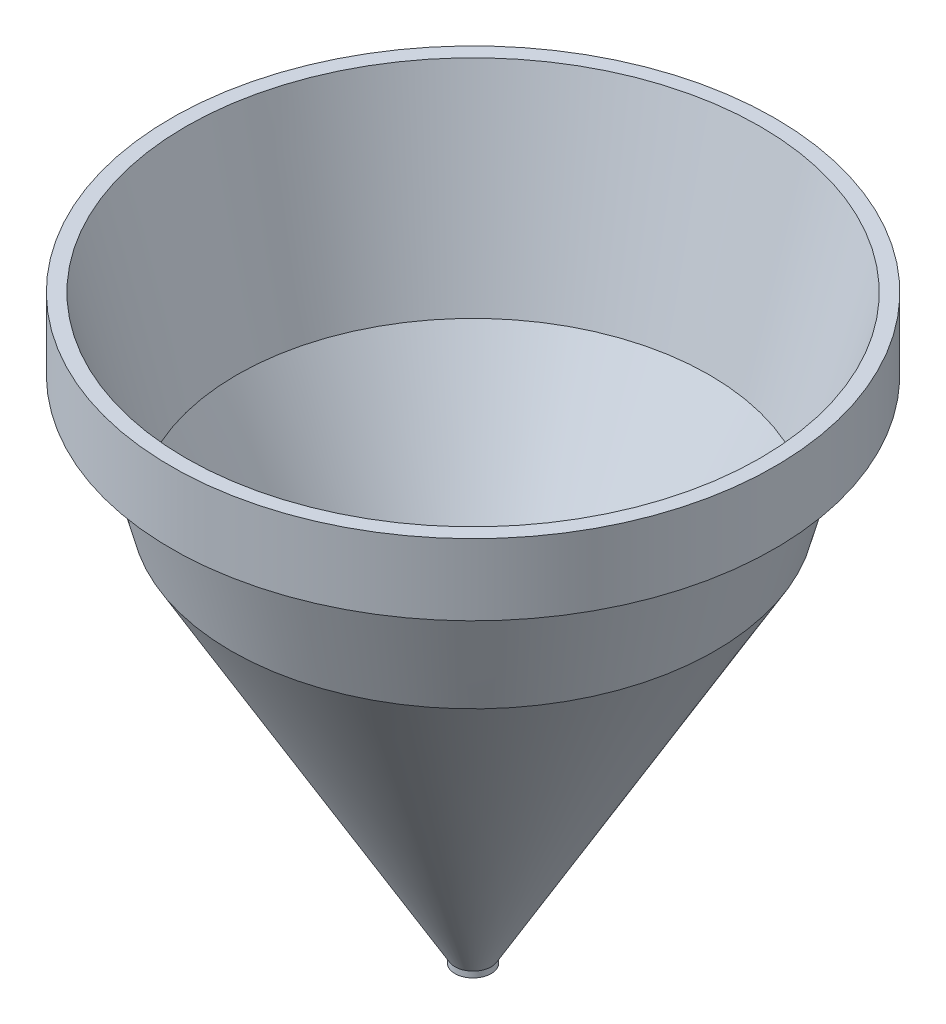
SolidWorks part; units mm, degrees
ref_plane "Piano frontale" through (0, 0, 0) normal (0, 0, 1) x (1, 0, 0)
ref_plane "Piano superiore" through (0, 0, 0) normal (0, 1, 0) x (1, 0, 0)
ref_plane "Piano destro" through (0, 0, 0) normal (1, 0, 0) x (0, 0, -1)
sketch "Schizzo1" plane through (0, 0, 0) normal (1, 0, 0) x (0, 0, -1)
  line L0 (0, 0) -> (0, 180) construction
  line L1 (0, 180) -> (-95, 180) construction
  line L2 (-95, 180) -> (-100, 180) construction
  line L3 (-95, 180) -> (-95, 130) construction
  line L4 (0, 0) -> (-4.25, 0) construction
  line L5 (-95, 180) -> (-81.6025, 130)
  line L6 (-100, 180) -> (-95, 180)
  line L7 (-100, 180) -> (-100, 170)
  line L8 (-100, 170) -> (-101.8, 170)
  line L9 (-101.8, 170) -> (-101.8, 194)
  line L10 (-93.2613, 180.4659) -> (-96.8878, 194)
  line L11 (-93.2613, 180.4659) -> (-79.739, 130)
  line L12 (-4.25, 0) -> (-79.739, 130)
  line L13 (-93.2613, 180.4659) -> (-105.0613, 224.5041) construction
  line L14 (-95, 180) -> (-106.8, 224.0382) construction
  line L15 (-95, 130) -> (-79.739, 130) construction
  line L16 (-93.2613, 180.4659) -> (-75.2309, 113.1753) construction
  line L17 (-95, 180) -> (-76.9695, 112.7094) construction
  line L18 (-81.6025, 130) -> (-6.1135, 0)
  line L19 (-4.25, 0) -> (-38.8422, 0) construction
  line L21 (-4.25, 0) -> (-4.25, -2)
  line L22 (-6.1135, 0) -> (-6.1135, -2)
  line L23 (-6.1135, -2) -> (-3.9656, -2)
  line L24 (-97.7803, 180) -> (-97.7803, 194) construction
  line L25 (-96.8878, 194) -> (-101.8, 194)
  dimension "D1" = 95
  dimension "D2" = 5
  dimension "D3" = 180
  dimension "D4" = 4.25
  dimension "D5" = 15
  dimension "D6" = 10
  dimension "D7" = 1.8
  dimension "D8" = 2
  dimension "D9" = 30.143
  dimension "D10" = 14
  dimension "D11" = 4.9122
revolve "Rivoluzione1" add sketch "Schizzo1" angle 360 about L0
